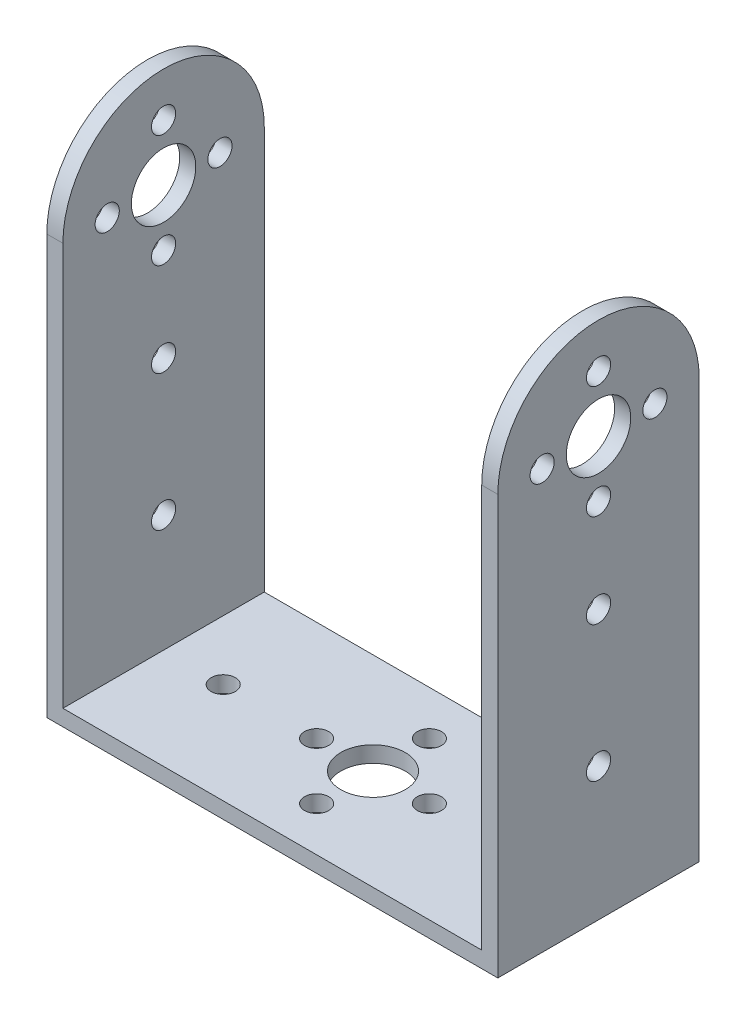
SolidWorks part; units mm, degrees
ref_plane "前视基准面" through (0, 0, 0) normal (0, 0, 1) x (1, 0, 0)
ref_plane "上视基准面" through (0, 0, 0) normal (0, 1, 0) x (1, 0, 0)
ref_plane "右视基准面" through (0, 0, 0) normal (1, 0, 0) x (0, 0, -1)
sketch "草图1" plane through (0, 0, 0) normal (0, 1, 0) x (1, 0, 0)
  line L1 (-20.3457, 13.2314) -> (35.6543, 13.2314)
  line L2 (-20.3457, 13.2314) -> (-20.3457, -11.7686)
  line L3 (-20.3457, -11.7686) -> (35.6543, -11.7686)
  line L4 (35.6543, 13.2314) -> (35.6543, -11.7686)
  dimension "D1" = 25
  dimension "D2" = 56
extrude "凸台-拉伸1" add sketch "草图1" along normal blind 2
sketch "草图2" plane through (0, 2, 0) normal (0, 1, 0) x (1, 0, 0)
  line L0 (7.6543, 13.2314) -> (7.6543, -11.7686) construction
  line L1 (35.6543, 13.2314) -> (-20.3457, 13.2314) construction
  line L2 (-20.3457, -11.7686) -> (35.6543, -11.7686) construction
  line L3 (-20.3457, 0.7314) -> (35.6543, 0.7314) construction
  line L4 (-20.3457, 13.2314) -> (-20.3457, -11.7686) construction
  line L5 (35.6543, -11.7686) -> (35.6543, 13.2314) construction
  circle A0 centre (7.6543, 0.7314) radius 4
  circle A1 centre (7.6543, 0.7314) radius 7 construction
  circle A2 centre (7.6543, 7.7314) radius 1.5
  circle A3 centre (14.6543, 0.7314) radius 1.5
  circle A4 centre (7.6543, -6.2686) radius 1.5
  circle A5 centre (0.6543, 0.7314) radius 1.5
  circle A6 centre (-10.9457, 0.7314) radius 1.5
  circle A7 centre (26.2543, 0.7314) radius 1.5
  point P26 (7.6543, 0.7314)
  dimension "D1" = 4
  dimension "D2" = 37.2
extrude "切除-拉伸1" cut sketch "草图2" against normal through all
sketch "草图3" plane through (-20.3457, 0, 0) normal (-1, 0, 0) x (0, 0, 1)
  line L0 (-13.2314, 2) -> (-13.2314, 22)
  line L2 (-13.2314, 22) -> (-13.2314, 52)
  line L3 (11.7686, 2) -> (11.7686, 22)
  line L4 (11.7686, 22) -> (11.7686, 52)
  line L5 (-13.2314, 2) -> (11.7686, 2)
  arc A0 (11.7686, 52) -> (-13.2314, 52) centre (-0.7314, 52) ccw
  dimension "D1" = 30
  dimension "D2" = 25
  dimension "D3" = 22
extrude "凸台-拉伸2" add sketch "草图3" against normal blind 2
sketch "草图4" plane through (-20.3457, 0, 0) normal (-1, 0, 0) x (0, 0, 1)
  line L0 (-13.2314, 52) -> (11.7686, 52) construction
  line L1 (-0.7314, 32) -> (-0.7314, 44.5) construction
  circle A0 centre (-0.7314, 16.53) radius 1.5
  circle A1 centre (-0.7314, 52) radius 4
  circle A2 centre (-0.7314, 59) radius 1.5
  circle A3 centre (6.2686, 52) radius 1.5
  circle A4 centre (-0.7314, 45) radius 1.5
  circle A5 centre (-7.7314, 52) radius 1.5
  circle A6 centre (-0.7314, 33.4) radius 1.5
  point P21 (-0.7314, 52)
  dimension "D1" = 7
  dimension "D3" = 18.6
  dimension "D4" = 16.87
  dimension "D2" = 4
extrude "切除-拉伸2" cut sketch "草图4" against normal up to next
ref_plane "基准面1" through (7.6543, 0, 0) normal (-1, 0, 0) x (0, 0, 1)
mirror "镜向1" about plane through (7.6543, 0, 0) normal (-1, 0, 0) of "切除-拉伸2", "凸台-拉伸2"
